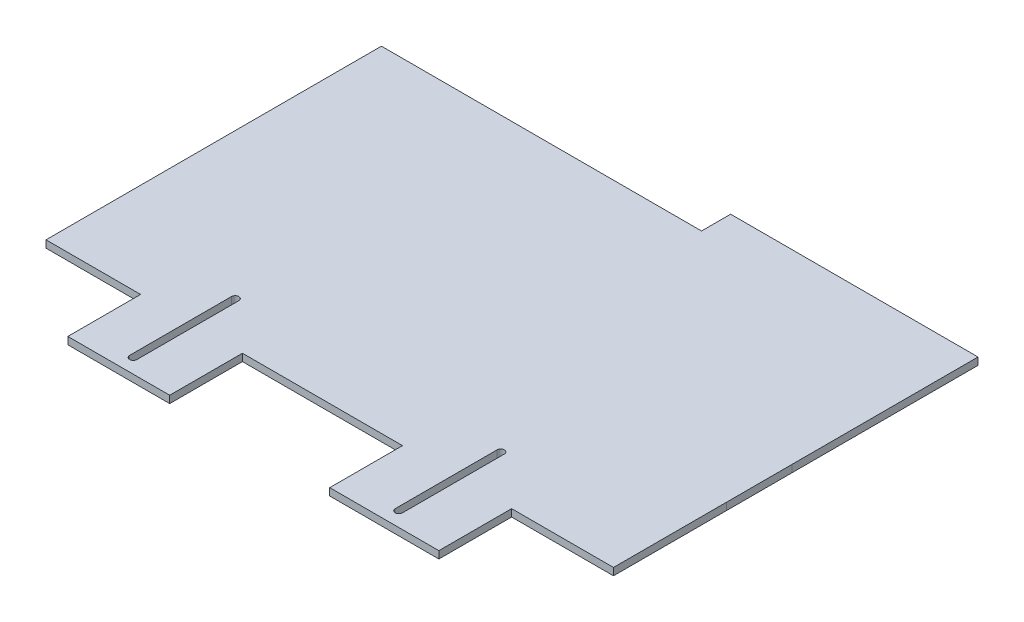
SolidWorks part; units mm, degrees
material "Acrylic (Medium-high impact)"
ref_plane "Front Plane" through (0, 0, 0) normal (0, 0, 1) x (1, 0, 0)
ref_plane "Top Plane" through (0, 0, 0) normal (0, 1, 0) x (1, 0, 0)
ref_plane "Right Plane" through (0, 0, 0) normal (1, 0, 0) x (0, 0, -1)
sketch "Sketch1" plane through (0, 0, 0) normal (0, 1, 0) x (1, 0, 0)
  line L1 (-247.65, -28.575) -> (247.65, -28.575)
  line L2 (-247.65, -28.575) -> (-247.65, 28.575)
  line L3 (-247.65, 28.575) -> (247.65, 28.575)
  line L4 (247.65, -28.575) -> (247.65, 28.575)
  line L5 (-247.65, -28.575) -> (247.65, 28.575) construction
  line L6 (-247.65, 28.575) -> (247.65, -28.575) construction
  line L7 (171.45, -28.575) -> (-31.75, -28.575)
  line L11 (-285.75, -28.575) -> (-133.35, -28.575)
  point P0 (0, 0)
  dimension "D1" = 495.3
  dimension "D2" = 57.15
extrude "Boss-Extrude1" add sketch "Sketch1" along normal mid plane 6.35 contours L1 L4 L3 L2
sketch "Sketch2" [suppressed] plane through (0, 0, 0) normal (0, 1, 0) x (1, 0, 0)
  line L0 (-247.65, -28.575) -> (247.65, -28.575) construction
  line L1 (158.75, -28.575) -> (63.5, -28.575)
  line L2 (158.75, -28.575) -> (158.75, -92.075)
  line L3 (158.75, -92.075) -> (63.5, -92.075)
  line L4 (63.5, -28.575) -> (63.5, -92.075)
  line L6 (-76.2, -28.575) -> (-165.1, -28.575)
  line L7 (-76.2, -28.575) -> (-76.2, -92.075)
  line L8 (-76.2, -92.075) -> (-165.1, -92.075)
  line L9 (-165.1, -28.575) -> (-165.1, -92.075)
  line L10 (247.65, -28.575) -> (247.65, 28.575) construction
  line L11 (-247.65, -28.575) -> (-247.65, 28.575) construction
  line L12 (-247.65, 28.575) -> (247.65, 28.575) construction
  line L13 (-247.65, -28.575) -> (-247.65, 28.575) construction
  point P19 (63.5, -92.075)
  dimension "D1" = 139.7
  dimension "D2" = 88.9
  dimension "D3" = 82.55
  dimension "D4" = 171.45
  dimension "D5" = 120.65
extrude "Boss-Extrude2" [suppressed] add sketch "Sketch2" along normal mid plane 6.35 contours L6 L9 L8 L7 | L2 L3 L4 L1
sketch "Sketch3" [suppressed] plane through (0, 3.175, 0) normal (0, 1, 0) x (1, 0, 0)
  line L0 (-149.225, 247.65) -> (149.225, 247.65) construction
  line L1 (-98.425, 12.7) -> (98.425, 12.7)
  line L2 (-98.425, 12.7) -> (-98.425, -101.6)
  line L3 (-98.425, -101.6) -> (98.425, -101.6)
  line L4 (98.425, 12.7) -> (98.425, -101.6)
  line L5 (-98.425, 12.7) -> (98.425, -101.6) construction
  line L6 (-98.425, -101.6) -> (98.425, 12.7) construction
  line L7 (-149.225, -247.65) -> (149.225, -247.65) construction
  point P0 (0, -44.45)
  point P7 (0, 247.65)
  point P8 (0, 12.7)
  dimension "D1" = 196.85
  dimension "D2" = 114.3
  dimension "D3" = 203.2
extrude "Cut-Extrude1" [suppressed] cut sketch "Sketch3" against normal through all and the other way through all
sketch "Sketch4" [suppressed] plane through (0, -3.175, 0) normal (0, -1, 0) x (1, 0, 0)
  line L0 (-107.315, 31.75) -> (107.315, 31.75) construction
  line L1 (-107.315, 33.9979) -> (107.315, 33.9979)
  line L2 (-107.315, 29.5021) -> (107.315, 29.5021)
  line L3 (-107.315, 6.35) -> (107.315, 6.35) construction
  line L4 (-107.315, 8.5979) -> (107.315, 8.5979)
  line L5 (-107.315, 4.1021) -> (107.315, 4.1021)
  arc A0 (-107.315, 33.9979) -> (-107.315, 29.5021) centre (-107.315, 31.75) ccw
  arc A1 (107.315, 29.5021) -> (107.315, 33.9979) centre (107.315, 31.75) ccw
  arc A2 (-107.315, 8.5979) -> (-107.315, 4.1021) centre (-107.315, 6.35) ccw
  arc A3 (107.315, 4.1021) -> (107.315, 8.5979) centre (107.315, 6.35) ccw
  point P0 (-107.315, 31.75)
  point P1 (107.315, 31.75)
  point P3 (107.315, 6.35)
  point P5 (-107.315, 6.35)
  point P10 (0, 31.75)
  point P15 (0, 6.35)
  dimension "D1" = 4.4958
  dimension "D2" = 4.4958
extrude "Cut-Extrude2" [suppressed] cut sketch "Sketch4" against normal through all
sketch "Sketch5" [suppressed] plane through (0, -3.175, 0) normal (0, -1, 0) x (1, 0, 0)
  line L0 (73.025, 79.375) -> (73.025, -9.525) construction
  line L1 (63.5, 28.575) -> (63.5, 92.075) construction
  line L2 (158.75, 92.075) -> (63.5, 92.075) construction
  line L3 (-247.65, -22.225) -> (247.65, -22.225) construction
  line L4 (73.025, 79.375) -> (73.025, -9.525) construction
  line L5 (75.2729, 79.375) -> (75.2729, -9.525)
  line L6 (70.7771, 79.375) -> (70.7771, -9.525)
  line L7 (-85.725, 79.375) -> (-85.725, -9.525) construction
  line L8 (-76.2, 28.575) -> (-76.2, 92.075) construction
  line L9 (-76.2, 92.075) -> (-165.1, 92.075) construction
  line L10 (-85.725, 79.375) -> (-85.725, -9.525) construction
  line L11 (-83.4771, 79.375) -> (-83.4771, -9.525)
  line L12 (-87.9729, 79.375) -> (-87.9729, -9.525)
  arc A0 (75.2729, 79.375) -> (70.7771, 79.375) centre (73.025, 79.375) ccw
  arc A1 (70.7771, -9.525) -> (75.2729, -9.525) centre (73.025, -9.525) ccw
  arc A2 (-83.4771, 79.375) -> (-87.9729, 79.375) centre (-85.725, 79.375) ccw
  arc A3 (-87.9729, -9.525) -> (-83.4771, -9.525) centre (-85.725, -9.525) ccw
  point P8 (73.025, 34.925)
  point P19 (-85.725, 34.925)
  dimension "D1" = 9.525
  dimension "D2" = 12.7
  dimension "D3" = 12.7
  dimension "D4" = 4.4958
  dimension "D5" = 9.525
  dimension "D6" = 12.7
  dimension "D7" = 12.7
  dimension "D8" = 4.4958
extrude "Cut-Extrude3" [suppressed] cut sketch "Sketch5" against normal through all contours L12 A3 L11 A2 | L6 A1 L5 A0
sketch "Sketch6" [suppressed] plane through (0, 3.175, 0) normal (0, 1, 0) x (1, 0, 0)
  line L0 (-79.375, -38.1) -> (-79.375, 38.1) construction
  line L1 (-88.9, -50.8) -> (-88.9, 50.8) construction
  line L2 (-88.9, -50.8) -> (88.9, -50.8) construction
  line L3 (-88.9, 50.8) -> (88.9, 50.8) construction
  line L4 (79.375, -38.1) -> (79.375, 38.1) construction
  line L5 (88.9, -50.8) -> (88.9, 50.8) construction
  line L6 (-79.375, -38.1) -> (-79.375, 38.1) construction
  line L7 (-81.6229, -38.1) -> (-81.6229, 38.1)
  line L8 (-77.1271, -38.1) -> (-77.1271, 38.1)
  line L9 (79.375, -38.1) -> (79.375, 38.1) construction
  line L10 (77.1271, -38.1) -> (77.1271, 38.1)
  line L11 (81.6229, -38.1) -> (81.6229, 38.1)
  arc A0 (-81.6229, -38.1) -> (-77.1271, -38.1) centre (-79.375, -38.1) ccw
  arc A1 (-77.1271, 38.1) -> (-81.6229, 38.1) centre (-79.375, 38.1) ccw
  arc A2 (77.1271, -38.1) -> (81.6229, -38.1) centre (79.375, -38.1) ccw
  arc A3 (81.6229, 38.1) -> (77.1271, 38.1) centre (79.375, 38.1) ccw
  point P12 (-79.375, 0)
  point P17 (79.375, 0)
  dimension "D1" = 9.525
  dimension "D2" = 12.7
  dimension "D3" = 12.7
  dimension "D4" = 9.525
  dimension "D5" = 12.7
  dimension "D6" = 12.7
  dimension "D7" = 4.4958
  dimension "D8" = 4.4958
extrude "Cut-Extrude4" [suppressed] cut sketch "Sketch6" against normal through all
sketch "Sketch7" [suppressed] plane through (0, 3.175, 0) normal (0, 1, 0) x (1, 0, 0)
  point P0 (115.1313, 66.802)
  point P1 (139.827, 42.1063)
  point P3 (-139.827, 42.1063)
  point P5 (-115.1313, 66.802)
hole_wizard "#12 Clearance Hole1" [suppressed] positions "Sketch8" profile "Sketch9" hole size "#12" standard "ANSI Inch"
sketch "Sketch8" [suppressed] plane through (0, 3.175, 0) normal (0, 1, 0) x (1, 0, 0)
  point P0 (-139.827, 42.1063)
  point P3 (-115.1313, 66.802)
  point P6 (115.1313, 66.802)
  point P9 (139.827, 42.1063)
sketch "Sketch9" plane through (-139.827, 3.175, -42.1063) normal (1, 0, 0) x (0, 0, 1)
  line L0 (0, 0) -> (0, 18.1964)
  line L1 (0, 18.1964) -> (2.8067, 16.51)
  line L2 (2.8067, 16.51) -> (2.8067, 0)
  line L5 (2.8067, 0) -> (0, 0)
  line L10 (0, 18.1964) -> (-2.8067, 16.51) construction
  line L11 (0, -6.35) -> (0, 107.95) construction
  dimension "Hole Dia." = 5.6134
  dimension "Hole Depth" = 16.51
  dimension "Drill Angle" = 118
sketch "Sketch10" [suppressed] plane through (0, -3.175, 0) normal (0, -1, 0) x (1, 0, 0)
  point P0 (223.8375, -6.35)
  point P1 (223.8375, 19.05)
  point P3 (-223.8375, 19.05)
  point P5 (-223.8375, -6.35)
hole_wizard "#12 Clearance Hole3" [suppressed] positions "Sketch11" profile "Sketch12" hole size "#12" standard "ANSI Inch"
sketch "Sketch11" [suppressed] plane through (0, -3.175, 0) normal (0, -1, 0) x (-1, 0, 0)
  point P0 (-223.8375, -19.05)
  point P3 (-223.8375, 6.35)
  point P6 (223.8375, -19.05)
  point P9 (223.8375, 6.35)
sketch "Sketch12" plane through (223.8375, -3.175, 19.05) normal (1, 0, 0) x (0, 0, -1)
  line L0 (0, 0) -> (0, 18.1964)
  line L1 (0, 18.1964) -> (2.8067, 16.51)
  line L2 (2.8067, 16.51) -> (2.8067, 0)
  line L5 (2.8067, 0) -> (0, 0)
  line L10 (0, 18.1964) -> (-2.8067, 16.51) construction
  line L11 (0, -6.35) -> (0, 107.95) construction
  dimension "Hole Dia." = 5.6134
  dimension "Hole Depth" = 16.51
  dimension "Drill Angle" = 118
sketch "Sketch13" [suppressed] plane through (0, -3.175, 0) normal (0, -1, 0) x (1, 0, 0)
  point P0 (133.35, -223.8375)
  point P1 (107.95, -223.8375)
  point P3 (-107.95, -223.8375)
  point P5 (-133.35, -223.8375)
  point P7 (133.35, 223.8375)
  point P9 (107.95, 223.8375)
  point P11 (-107.95, 223.8375)
  point P13 (-133.35, 223.8375)
hole_wizard "#12 Clearance Hole2" [suppressed] positions "Sketch14" profile "Sketch15" hole size "#12" standard "ANSI Inch"
sketch "Sketch14" [suppressed] plane through (0, -3.175, 0) normal (0, -1, 0) x (-1, 0, 0)
  point P0 (107.95, -223.8375)
  point P3 (133.35, -223.8375)
  point P6 (133.35, 223.8375)
  point P9 (107.95, 223.8375)
  point P12 (-133.35, 223.8375)
  point P15 (-107.95, 223.8375)
  point P18 (-133.35, -223.8375)
  point P21 (-107.95, -223.8375)
sketch "Sketch15" plane through (-107.95, -3.175, 223.8375) normal (1, 0, 0) x (0, 0, -1)
  line L0 (0, 0) -> (0, 18.1964)
  line L1 (0, 18.1964) -> (2.8067, 16.51)
  line L2 (2.8067, 16.51) -> (2.8067, 0)
  line L5 (2.8067, 0) -> (0, 0)
  line L10 (0, 18.1964) -> (-2.8067, 16.51) construction
  line L11 (0, -6.35) -> (0, 107.95) construction
  dimension "Hole Dia." = 5.6134
  dimension "Hole Depth" = 16.51
  dimension "Drill Angle" = 118
sketch "Sketch16" [suppressed] plane through (0, 3.175, 0) normal (0, 1, 0) x (1, 0, 0)
  line L0 (88.9, -50.8) -> (88.9, 50.8) construction
  line L1 (-88.9, -50.8) -> (-88.9, 50.8) construction
  line L2 (-88.9, -50.8) -> (88.9, -50.8) construction
  point P0 (79.375, -38.1)
  point P1 (-79.375, -38.1)
  dimension "D1" = 9.525
  dimension "D2" = 9.525
  dimension "D3" = 12.7
hole_wizard "#8 Clearance Hole1" [suppressed] positions "Sketch17" profile "Sketch19" hole size "#8" standard "ANSI Inch"
sketch "Sketch17" [suppressed] plane through (0, 3.175, 0) normal (0, 1, 0) x (1, 0, 0)
  point P0 (79.375, -38.1)
  point P3 (-79.375, -38.1)
sketch "Sketch19" plane through (79.375, 3.175, 38.1) normal (1, 0, 0) x (0, 0, 1)
  line L0 (0, 0) -> (0, 12.0187)
  line L1 (0, 12.0187) -> (2.2479, 10.668)
  line L2 (2.2479, 10.668) -> (2.2479, 0)
  line L5 (2.2479, 0) -> (0, 0)
  line L10 (0, 12.0187) -> (-2.2479, 10.668) construction
  line L11 (0, -6.35) -> (0, 107.95) construction
  dimension "Hole Dia." = 4.4958
  dimension "Hole Depth" = 10.668
  dimension "Drill Angle" = 118
sketch "Sketch20" [suppressed] plane through (0, -3.175, 0) normal (0, -1, 0) x (1, 0, 0)
  line L0 (-149.225, 247.65) -> (149.225, 247.65) construction
  line L1 (23.9395, 147.5105) -> (-23.9395, 147.5105)
  line L2 (23.9395, 147.5105) -> (23.9395, 195.3895)
  line L3 (23.9395, 195.3895) -> (-23.9395, 195.3895)
  line L4 (-23.9395, 147.5105) -> (-23.9395, 195.3895)
  line L5 (23.9395, 147.5105) -> (-23.9395, 195.3895) construction
  line L6 (23.9395, 195.3895) -> (-23.9395, 147.5105) construction
  line L8 (38.1, 155.575) -> (-38.1, 155.575) construction
  line L9 (38.1, 155.575) -> (38.1, 187.325) construction
  line L10 (38.1, 187.325) -> (-38.1, 187.325) construction
  line L11 (-38.1, 155.575) -> (-38.1, 187.325) construction
  point P0 (0, 171.45)
  point P7 (0, 247.65)
  point P8 (38.1, 155.575)
  point P9 (38.1, 187.325)
  point P10 (-38.1, 155.575)
  point P11 (-38.1, 187.325)
  point P18 (0, 187.325)
  point P19 (0, 195.3895)
  point P20 (-38.1, 171.45)
  point P21 (-23.9395, 171.45)
  dimension "D1" = 47.879
  dimension "D2" = 47.879
  dimension "D3" = 38.1
  dimension "D4" = 15.875
  dimension "D5" = 76.2
extrude "Cut-Extrude5" [suppressed] cut sketch "Sketch20" against normal through all contours L1 L4 L3 L2
hole_wizard "#10 Clearance Hole1" [suppressed] positions "Sketch21" profile "Sketch22" hole size "#10" standard "ANSI Inch"
sketch "Sketch21" [suppressed] plane through (0, -3.175, 0) normal (0, -1, 0) x (-1, 0, 0)
  point P0 (-38.1, -155.575)
  point P3 (38.1, -155.575)
  point P6 (38.1, -187.325)
  point P9 (-38.1, -187.325)
sketch "Sketch22" plane through (38.1, -3.175, 155.575) normal (1, 0, 0) x (0, 0, -1)
  line L0 (0, 0) -> (0, 12.2018)
  line L1 (0, 12.2018) -> (2.5527, 10.668)
  line L2 (2.5527, 10.668) -> (2.5527, 0)
  line L5 (2.5527, 0) -> (0, 0)
  line L10 (0, 12.2018) -> (-2.5527, 10.668) construction
  line L11 (0, -6.35) -> (0, 107.95) construction
  dimension "Hole Dia." = 5.1054
  dimension "Hole Depth" = 10.668
  dimension "Drill Angle" = 118
sketch "Sketch23" plane through (0, 0, 0) normal (0, 1, 0) x (1, 0, 0)
  line L1 (-247.663, -190.825) -> (247.637, -190.825)
  line L2 (-247.663, -190.825) -> (-247.663, 190.825)
  line L3 (-247.663, 190.825) -> (247.637, 190.825)
  line L4 (247.637, -190.825) -> (247.637, 190.825)
  line L5 (-247.663, -190.825) -> (247.637, 190.825) construction
  line L6 (-247.663, 190.825) -> (247.637, -190.825) construction
  line L7 (-3.4925, 0) -> (3.4925, 0) construction
  point P0 (-0.013, 0)
  dimension "D1" = 495.3
  dimension "D2" = 381.65
extrude "Boss-Extrude3" add sketch "Sketch23" along normal mid plane 6.35
sketch "Sketch24" plane through (0, 3.175, 0) normal (0, 1, 0) x (1, 0, 0)
  line L0 (247.637, -190.825) -> (247.637, -28.575) construction
  line L1 (158.737, -127.325) -> (247.637, -127.325)
  line L2 (158.737, -127.325) -> (158.737, -190.825)
  line L3 (158.737, -190.825) -> (247.637, -190.825)
  line L4 (247.637, -127.325) -> (247.637, -190.825)
  line L5 (158.737, -127.325) -> (247.637, -190.825) construction
  line L6 (158.737, -190.825) -> (247.637, -127.325) construction
  line L7 (-247.663, -190.825) -> (247.637, -190.825) construction
  line L8 (-247.663, 190.825) -> (-247.663, -190.825) construction
  line L9 (-76.213, -190.825) -> (63.487, -190.825)
  line L10 (-76.213, -190.825) -> (-76.213, -127.325)
  line L11 (-76.213, -127.325) -> (63.487, -127.325)
  line L12 (63.487, -190.825) -> (63.487, -127.325)
  line L13 (-76.213, -190.825) -> (63.487, -127.325) construction
  line L14 (-76.213, -127.325) -> (63.487, -190.825) construction
  line L15 (-165.113, -127.325) -> (-247.663, -127.325)
  line L16 (-165.113, -127.325) -> (-165.113, -190.825)
  line L17 (-165.113, -190.825) -> (-247.663, -190.825)
  line L18 (-247.663, -127.325) -> (-247.663, -190.825)
  line L19 (-165.113, -127.325) -> (-247.663, -190.825) construction
  line L20 (-165.113, -190.825) -> (-247.663, -127.325) construction
  point P0 (203.187, -159.075)
  point P9 (-6.363, -159.075)
  point P14 (-206.388, -159.075)
  dimension "D1" = 63.5
  dimension "D2" = 88.9
  dimension "D3" = 95.25
  dimension "D4" = 139.7
  dimension "D5" = 88.9
extrude "Cut-Extrude6" cut sketch "Sketch24" against normal blind 6.35
sketch "Sketch25" plane through (0, 3.175, 0) normal (0, 1, 0) x (1, 0, 0)
  line L0 (111.112, -89.225) -> (111.112, -178.125) construction
  line L1 (114.287, -89.225) -> (114.287, -178.125)
  line L2 (107.937, -89.225) -> (107.937, -178.125)
  line L3 (-120.663, -89.225) -> (-120.663, -178.125) construction
  line L4 (-117.488, -89.225) -> (-117.488, -178.125)
  line L5 (-123.838, -89.225) -> (-123.838, -178.125)
  line L6 (63.487, -190.825) -> (158.737, -190.825) construction
  line L7 (-165.113, -190.825) -> (-76.213, -190.825) construction
  arc A0 (114.287, -89.225) -> (107.937, -89.225) centre (111.112, -89.225) ccw
  arc A1 (107.937, -178.125) -> (114.287, -178.125) centre (111.112, -178.125) ccw
  arc A2 (-117.488, -89.225) -> (-123.838, -89.225) centre (-120.663, -89.225) ccw
  arc A3 (-123.838, -178.125) -> (-117.488, -178.125) centre (-120.663, -178.125) ccw
  point P2 (111.112, -133.675)
  point P7 (-120.663, -133.675)
  point P18 (111.112, -190.825)
  point P19 (-120.663, -190.825)
  dimension "D1" = 12.7
  dimension "D2" = 12.7
  dimension "D3" = 6.35
  dimension "D4" = 6.35
  dimension "D5" = 88.9
  dimension "D6" = 88.9
extrude "Cut-Extrude7" cut sketch "Sketch25" against normal blind 6.35
sketch "Sketch26" [suppressed] plane through (0, 0, 0) normal (0, 1, 0) x (1, 0, 0)
  line L1 (-190.825, 152.35) -> (190.825, 152.35)
  line L2 (-190.825, 152.35) -> (-190.825, -152.35)
  line L3 (-190.825, -152.35) -> (190.825, -152.35)
  line L4 (190.825, 152.35) -> (190.825, -152.35)
  line L5 (-190.825, 152.35) -> (190.825, -152.35) construction
  line L6 (-190.825, -152.35) -> (190.825, 152.35) construction
  point P0 (0, 0)
  dimension "D1" = 304.7
  dimension "D2" = 304.8
extrude "Boss-Extrude4" [suppressed] add sketch "Sketch26" along normal blind 6.35
sketch "Sketch27" plane through (0, 3.175, 0) normal (0, 1, 0) x (1, 0, 0)
  line L1 (31.737, 165.425) -> (-247.663, 165.425)
  line L2 (31.737, 165.425) -> (31.737, 190.825)
  line L3 (31.737, 190.825) -> (-247.663, 190.825)
  line L4 (-247.663, 165.425) -> (-247.663, 190.825)
  line L5 (31.737, 165.425) -> (-247.663, 190.825) construction
  line L6 (31.737, 190.825) -> (-247.663, 165.425) construction
  point P0 (-107.963, 178.125)
  dimension "D1" = 279.4
  dimension "D2" = 25.4
extrude "Cut-Extrude8" cut sketch "Sketch27" against normal blind 6.35
